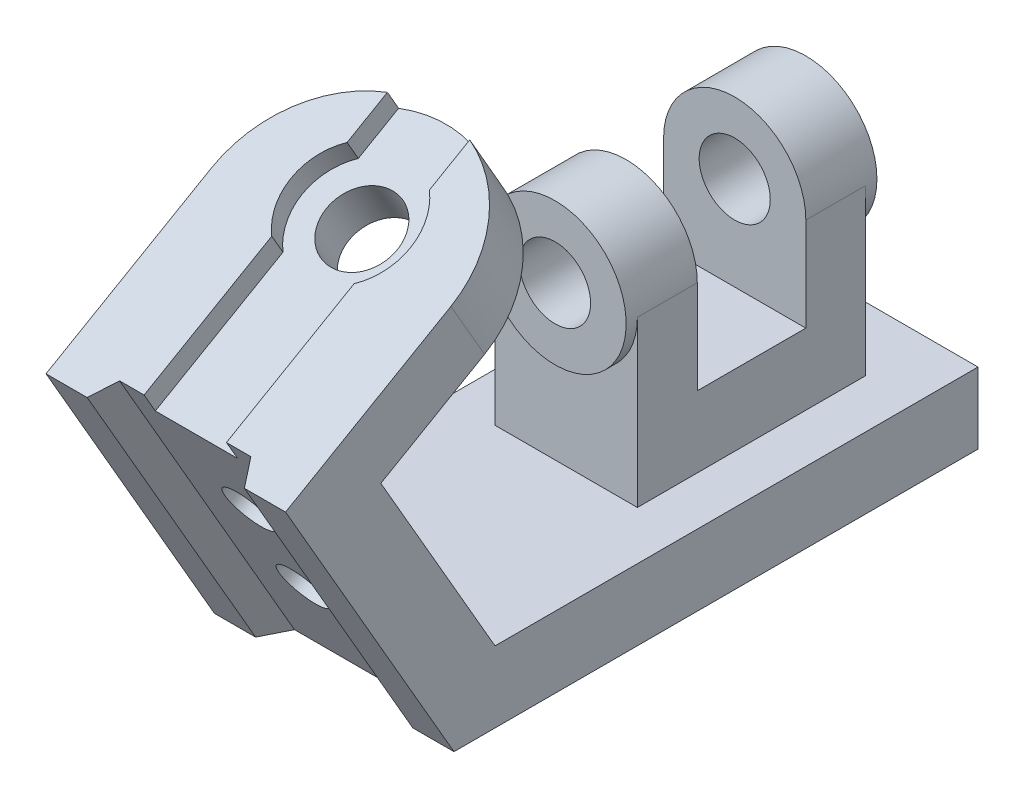
SolidWorks part; units mm, degrees
material "___"
ref_plane "Front Plane" through (0, 0, 0) normal (0, 0, 1) x (1, 0, 0)
ref_plane "Top Plane" through (0, 0, 0) normal (0, 1, 0) x (1, 0, 0)
ref_plane "Right Plane" through (0, 0, 0) normal (1, 0, 0) x (0, 0, -1)
sketch "Sketch1" plane through (0, 0, 0) normal (1, 0, 0) x (0, 0, -1)
  line L0 (0, 0) -> (140, 0)
  line L2 (0, 0) -> (-45, 77.9423)
  dimension "D1" = 140
  dimension "D2" = 90
  dimension "D3" = 60
extrude "Extrude-Thin1" add sketch "Sketch1" along normal blind 64 thin thin type one direction wall 19
sketch "Sketch2" plane through (0, 77.9423, 45) normal (0, 0.866, 0.5) x (1, 0, 0)
  line L0 (0, 0) -> (0, 51)
  line L1 (64, 51) -> (64, 0)
  line L2 (64, 0) -> (0, 0)
  arc A0 (0, 51) -> (64, 51) centre (32, 51) cw
  dimension "D2" = 32
  dimension "D1" = 51
extrude "Boss-Extrude1" add sketch "Sketch2" against normal blind 18
ref_plane "Plane1" through (32, 0, 0) normal (1, 0, 0) x (0, 0, -1)
sketch "Sketch3" plane through (32, 0, 0) normal (1, 0, 0) x (0, 0, -1)
  line L0 (140, 19) -> (10.9697, 19) construction
  line L1 (62, 19) -> (123, 19)
  line L2 (62, 19) -> (62, 63)
  line L3 (62, 63) -> (123, 63)
  line L4 (123, 19) -> (123, 63)
  line L5 (140, 19) -> (140, 0) construction
  dimension "D1" = 17
  dimension "D2" = 44
  dimension "D3" = 61
extrude "Boss-Extrude2" add sketch "Sketch3" along normal mid plane 38
sketch "Sketch4" plane through (51, 0, 0) normal (1, 0, 0) x (0, 0, -1)
  line L0 (123, 63) -> (62, 63) construction
  line L1 (78, 63) -> (107, 63)
  line L2 (78, 63) -> (78, 38)
  line L3 (78, 38) -> (107, 38)
  line L4 (107, 63) -> (107, 38)
  line L5 (62, 63) -> (62, 19) construction
  dimension "D1" = 29
  dimension "D2" = 25
  dimension "D3" = 16
extrude "Cut-Extrude1" cut sketch "Sketch4" against normal through all
sketch "Sketch5" plane through (0, 0, -107) normal (0, 0, 1) x (1, 0, 0)
  line L0 (13, 63) -> (51, 63) construction
  circle A0 centre (32, 63) radius 19
extrude "Cut-Extrude2" cut sketch "Sketch5" against normal through all and the other way blind 55
sketch "Sketch6" plane through (0, 0, -107) normal (0, 0, 1) x (1, 0, 0)
  circle A0 centre (32, 63) radius 19
  arc A1 (13, 63) -> (51, 63) centre (32, 63) ccw construction
extrude "Boss-Extrude3" add sketch "Sketch6" against normal blind 19
sketch "Sketch8" plane through (0, 0, -78) normal (0, 0, -1) x (-1, 0, 0)
  circle A0 centre (-32, 63) radius 19
  arc A1 (-51, 63) -> (-13, 63) centre (-32, 63) ccw construction
extrude "Boss-Extrude4" add sketch "Sketch8" against normal blind 19
sketch "Sketch9" plane through (0, 0, -59) normal (0, 0, 1) x (1, 0, 0)
  circle A0 centre (32, 63) radius 9.5
  circle A1 centre (32, 63) radius 19 construction
  dimension "D1" = 19
extrude "Cut-Extrude3" cut sketch "Sketch9" against normal through all
sketch "Sketch10" plane through (0, 62.3538, 36) normal (0, -0.866, -0.5) x (-1, 0, 0)
  line L6 (-15.8973, 10.3117) -> (-15.8973, 66.616) construction
sketch "Sketch15" plane through (0, 77.9423, 45) normal (0, 0.866, 0.5) x (1, 0, 0)
  line L0 (32, 0) -> (32, 42.69) construction
  line L1 (64, 0) -> (0, 0) construction
  line L2 (11, 0) -> (14.4641, 6)
  line L3 (14.4641, 6) -> (49.5359, 6)
  line L4 (53, 0) -> (49.5359, 6)
  line L5 (11, 0) -> (53, 0)
  point P8 (32, 6)
  point P10 (52.2836, 0)
  dimension "D1" = 11
  dimension "D2" = 42
  dimension "D3" = 6
  dimension "D4" = 60
extrude "Cut-Extrude8" cut sketch "Sketch15" against normal through all contours L4 L3 L2 L5
sketch "Sketch16" plane through (0, 77.9423, 45) normal (0, 0.866, 0.5) x (1, 0, 0)
  line L0 (14.4641, 6) -> (49.5359, 6) construction
  line L1 (21.0141, 6) -> (43.0141, 6)
  line L2 (21.0141, 6) -> (21.0141, 86)
  line L3 (21.0141, 86) -> (43.0141, 86)
  line L4 (43.0141, 6) -> (43.0141, 86)
  dimension "D1" = 6.55
  dimension "D2" = 22
  dimension "D3" = 80
extrude "Cut-Extrude9" cut sketch "Sketch16" against normal blind 6
sketch "Sketch17" plane through (0, 77.9423, 45) normal (0, 0.866, 0.5) x (1, 0, 0)
  line L0 (21.0141, 6) -> (43.0141, 6) construction
  circle A0 centre (32.0141, 57) radius 16
  point P4 (32.95, 57)
  point P5 (32.0141, 6)
  dimension "D1" = 32
  dimension "D2" = 51
extrude "Cut-Extrude10" cut sketch "Sketch17" against normal blind 6
sketch "Sketch18" plane through (0, 72.7461, 42) normal (0, 0.866, 0.5) x (1, 0, 0)
  circle A0 centre (32.0141, 57) radius 9.5
  dimension "D1" = 19
extrude "Cut-Extrude11" cut sketch "Sketch18" against normal blind 19
sketch "Sketch19" plane through (0, 3, -5.1962) normal (0, -0.5, 0.866) x (1, 0, 0)
  line L1 (21.0141, 84) -> (43.0141, 84) construction
  circle A0 centre (32.0141, 56) radius 6.5
  circle A1 centre (32.0141, 27) radius 6.5
  point P4 (0, 0)
  point P9 (32.0141, 84)
  dimension "D1" = 13
  dimension "D2" = 28
  dimension "D3" = 29
extrude "Cut-Extrude12" cut sketch "Sketch19" against normal blind 19
